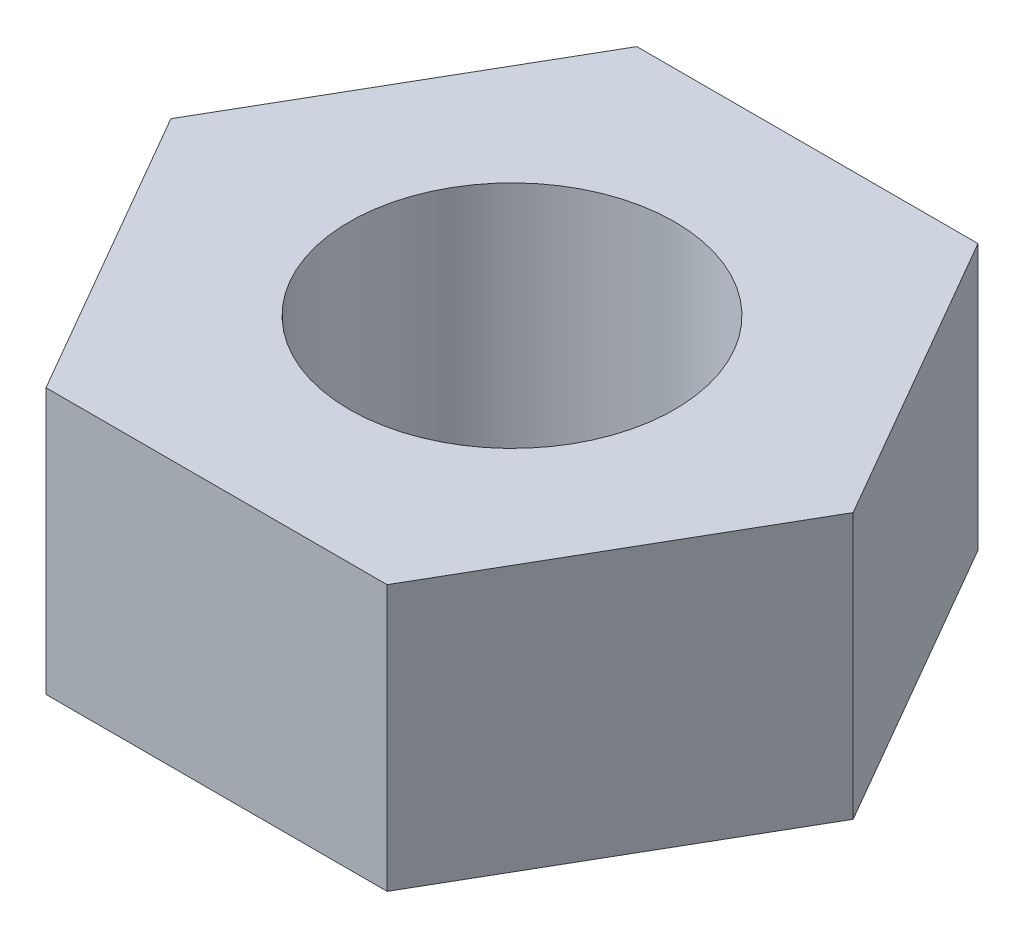
SolidWorks part; units mm, degrees
ref_plane "前视基准面" through (0, 0, 0) normal (0, 0, 1) x (1, 0, 0)
ref_plane "上视基准面" through (0, 0, 0) normal (0, 1, 0) x (1, 0, 0)
ref_plane "右视基准面" through (0, 0, 0) normal (1, 0, 0) x (0, 0, -1)
other "Configuration Table"
sketch "草图1" plane through (0, 0, 0) normal (0, 1, 0) x (1, 0, 0)
  line L1 (3.1466, 0) -> (1.5733, 2.725)
  line L2 (1.5733, 2.725) -> (-1.5733, 2.725)
  line L3 (-1.5733, 2.725) -> (-3.1466, 0)
  line L4 (-3.1466, 0) -> (-1.5733, -2.725)
  line L5 (-1.5733, -2.725) -> (1.5733, -2.725)
  line L6 (1.5733, -2.725) -> (3.1466, 0)
  circle A0 centre (0, 0) radius 2.725 construction
  circle A1 centre (0, 0) radius 1.5
  dimension "D2" = 3
  dimension "D1" = 5.45
extrude "凸台-拉伸1" add sketch "草图1" along normal blind 2.45
